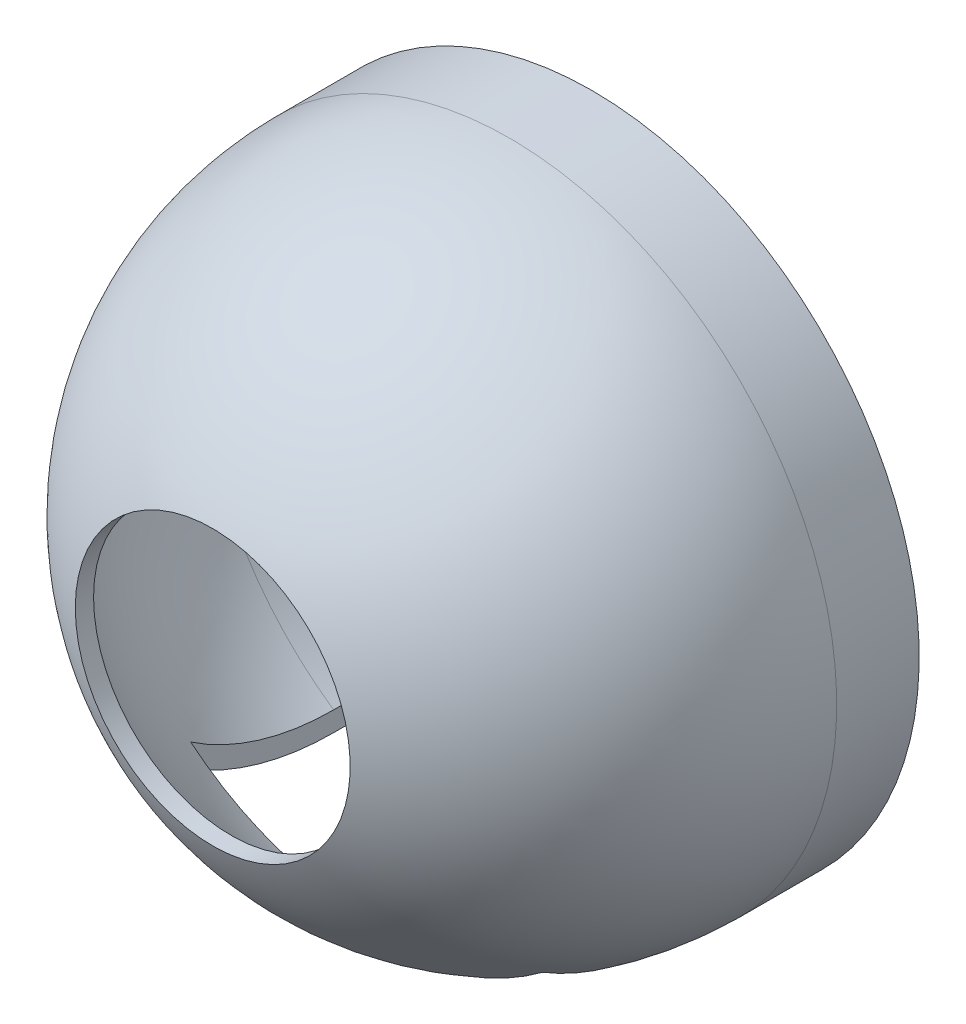
SolidWorks part; units mm, degrees
ref_plane "Front Plane" through (0, 0, 0) normal (0, 0, 1) x (1, 0, 0)
ref_plane "Top Plane" through (0, 0, 0) normal (0, 1, 0) x (1, 0, 0)
ref_plane "Right Plane" through (0, 0, 0) normal (1, 0, 0) x (0, 0, -1)
sketch "Sketch2" plane through (0, 0, 0) normal (1, 0, 0) x (0, 0, -1)
  line L7 (76.0803, 0) -> (147.5803, 0)
  line L8 (147.5803, 0) -> (147.5803, 56.5)
  line L9 (147.5803, 56.5) -> (132.5803, 56.5)
  line L10 (132.5803, 56.5) -> (132.5803, 0) construction
  line L11 (76.0803, 0) -> (46.7658, 0) construction
  arc A1 (132.5803, 56.5) -> (76.0803, 0) centre (132.5803, 0) ccw
  dimension "D4" = 56.5
  dimension "D3" = 15
revolve "Revolve1" add sketch "Sketch2" angle 360 about L11
shell "Shell1" thickness 3
sketch "Sketch5" plane through (0, 0, 0) normal (0, 0, 1) x (1, 0, 0)
  circle A0 centre (0, 0) radius 25
  dimension "D1" = 50
extrude "Cut-Extrude3" cut sketch "Sketch5" against normal through all
sketch "Sketch6" plane through (0, 0, 0) normal (0, 1, 0) x (1, 0, 0)
  line L0 (-59.5, 147.5803) -> (59.5, 147.5803) construction
  line L1 (0, 147.5803) -> (0, 116.2972) construction
  line L3 (-32, 147.5803) -> (32, 147.5803)
  line L4 (-32, 147.5803) -> (-32, 106.5803)
  line L5 (-32, 106.5803) -> (32, 106.5803)
  line L6 (32, 147.5803) -> (32, 106.5803)
  point P11 (0, 147.5803)
  dimension "D1" = 64
  dimension "D2" = 41
extrude "Cut-Extrude4" cut sketch "Sketch6" against normal through all
